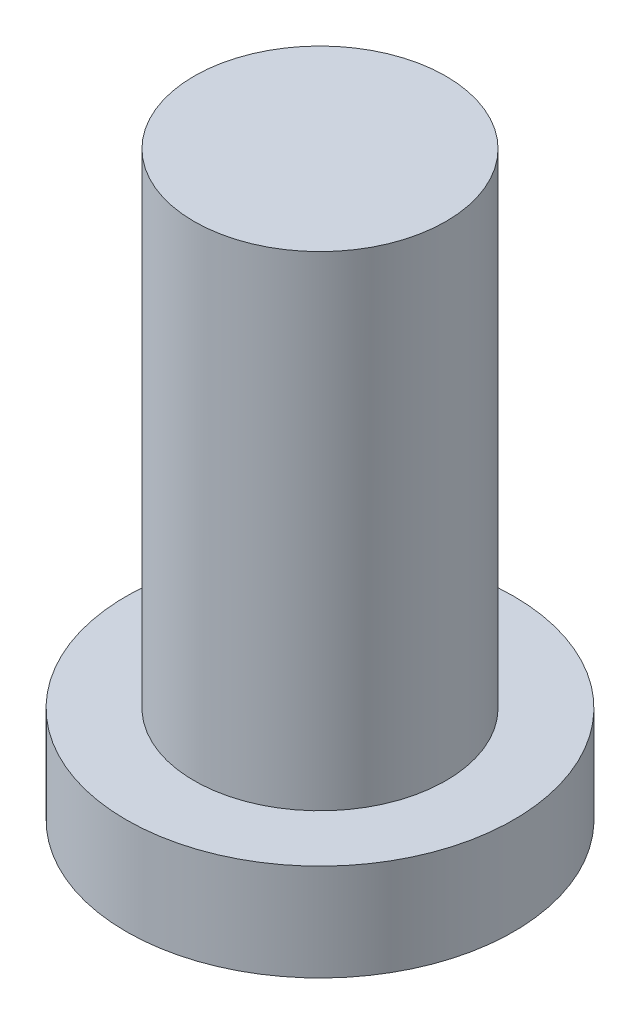
SolidWorks part; units mm, degrees
ref_plane "Front Plane" through (0, 0, 0) normal (0, 0, 1) x (1, 0, 0)
ref_plane "Top Plane" through (0, 0, 0) normal (0, 1, 0) x (1, 0, 0)
ref_plane "Right Plane" through (0, 0, 0) normal (1, 0, 0) x (0, 0, -1)
sketch "Sketch1" plane through (0, 0, 0) normal (0, 1, 0) x (1, 0, 0)
  circle A0 centre (0, 0) radius 1.3
  dimension "D1" = 2.6
extrude "Boss-Extrude1" add sketch "Sketch1" along normal blind 5
sketch "Sketch2" plane through (0, 0, 0) normal (0, -1, 0) x (1, 0, 0)
  circle A0 centre (0, 0) radius 2
extrude "Boss-Extrude2" add sketch "Sketch2" along normal blind 1
